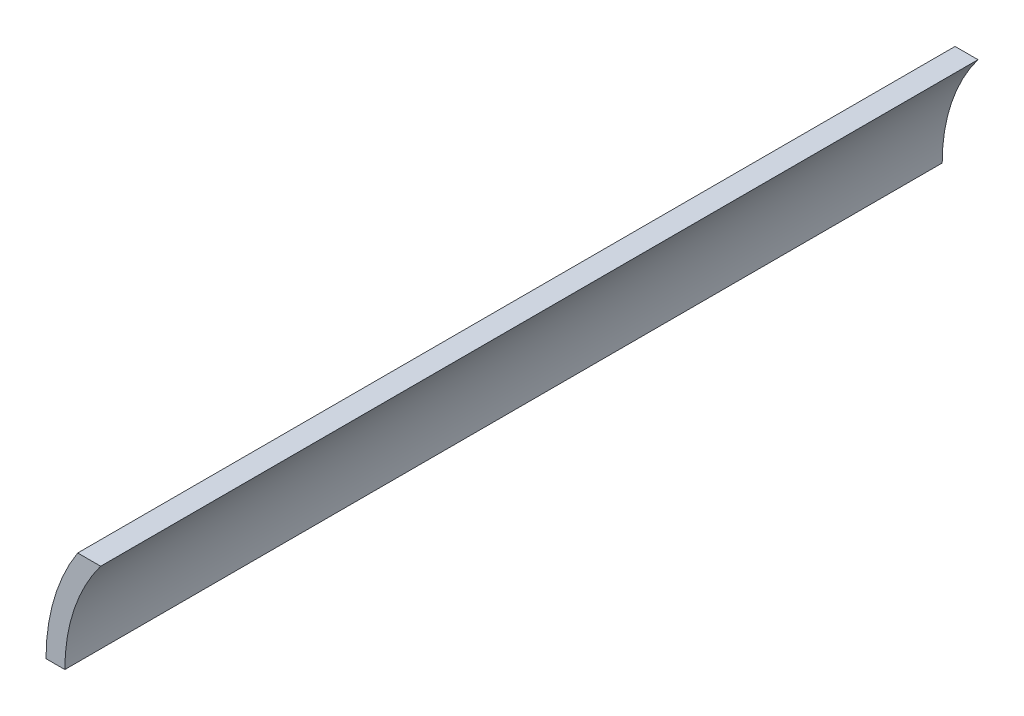
SolidWorks part; units mm, degrees
ref_plane "Plan de face" through (0, 0, 0) normal (0, 0, 1) x (1, 0, 0)
ref_plane "Plan de dessus" through (0, 0, 0) normal (0, 1, 0) x (1, 0, 0)
ref_plane "Plan de droite" through (0, 0, 0) normal (1, 0, 0) x (0, 0, -1)
sketch "Esquisse1" plane through (0, 0, 0) normal (0, 0, 1) x (1, 0, 0)
  line L0 (0, 0) -> (-81.2571, 0) construction
  line L1 (-90.367, 30) -> (23.3503, 30) construction
  line L2 (-46.4068, 30) -> (-40, 30)
  line L3 (-50, 0) -> (-55.2593, 0)
  arc A0 (-50, 0) -> (-40, 30) centre (0, 0) cw
  arc A1 (-55.2593, 0) -> (-46.4068, 30) centre (0, 0) cw
  point P7 (-47.4342, 15.8114)
  point P10 (-53, 15.6394)
  dimension "D1" = 30
  dimension "D2" = 50
  dimension "D3" = 53
extrude "Boss.-Extru.1" add sketch "Esquisse1" along normal blind 245
